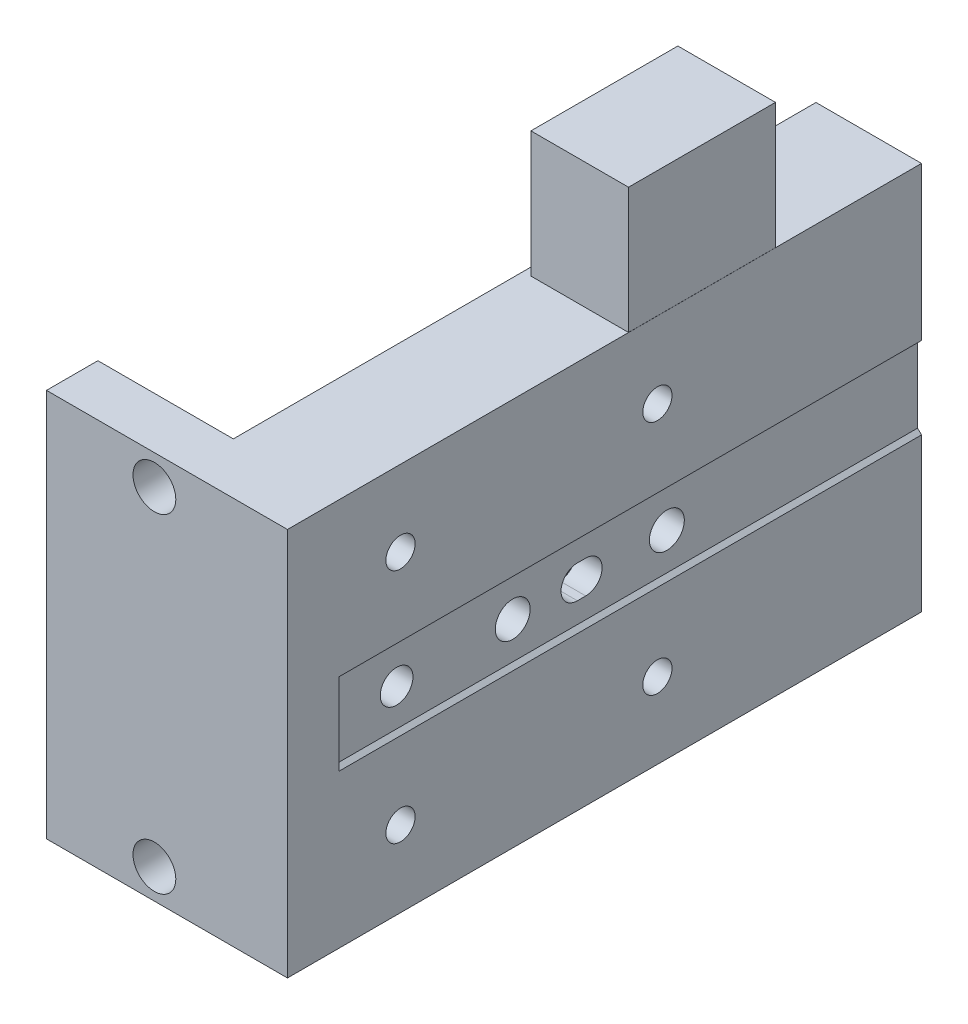
SolidWorks part; units mm, degrees
ref_plane "Front" through (0, 0, 0) normal (0, 0, 1) x (1, 0, 0)
ref_plane "Top" through (0, 0, 0) normal (0, 1, 0) x (1, 0, 0)
ref_plane "Right" through (0, 0, 0) normal (1, 0, 0) x (0, 0, -1)
sketch "Sketch1" plane through (0, 0, -942.5686) normal (0, 0, 1) x (1, 0, 0)
  line L0 (6.9596, 18.9) -> (-6.9596, 18.9) construction
  line L1 (-5.8406, 18.9) -> (17.6094, 18.9)
  line L2 (-5.8406, 18.9) -> (-5.8406, -18.9)
  line L3 (-5.8406, -18.9) -> (17.6094, -18.9)
  line L4 (17.6094, 18.9) -> (17.6094, 3.98)
  line L5 (-5.8406, 0) -> (17.2294, 0) construction
  line L6 (-7.3406, 18.519) -> (-7.3406, 7.3914) construction
  line L8 (-1.7907, -18.9) -> (1.7907, -18.9) construction
  line L9 (17.2294, 3.6) -> (17.2294, -3.6)
  line L10 (17.2294, -3.6) -> (17.6094, -3.98)
  line L11 (17.2294, 3.6) -> (17.6094, 3.98)
  line L12 (17.6094, -3.98) -> (17.6094, -18.9)
  dimension "D1" = 1.5
  dimension "D2" = 24.95
  dimension "D3" = 45
  dimension "D4" = 0.38
  dimension "D5" = 7.2
extrude "Base-Extrude" add sketch "Sketch1" along normal up to surface (5 mm away)
sketch "Sketch3" plane through (0, 0, -942.5686) normal (0, 0, -1) x (-1, 0, 0)
  line L0 (-17.6094, 3.98) -> (-17.6094, 18.9) construction
  line L1 (-17.6094, 18.9) -> (5.8406, 18.9) construction
  line L2 (-17.6094, 3.98) -> (-17.6094, 18.9)
  line L3 (-17.6094, 18.9) -> (-7.3406, 18.9)
  line L4 (5.8406, -18.9) -> (-17.6094, -18.9) construction
  line L5 (-17.6094, -18.9) -> (-17.6094, -3.98) construction
  line L6 (-17.6094, -3.98) -> (-17.2294, -3.6) construction
  line L7 (-17.2294, -3.6) -> (-17.2294, 3.6) construction
  line L8 (-17.2294, 3.6) -> (-17.6094, 3.98) construction
  line L9 (-7.3406, -18.9) -> (-17.6094, -18.9)
  line L10 (-17.6094, -18.9) -> (-17.6094, -3.98)
  line L11 (-17.6094, -3.98) -> (-17.2294, -3.6)
  line L12 (-17.2294, -3.6) -> (-17.2294, 3.6)
  line L13 (-17.2294, 3.6) -> (-17.6094, 3.98)
  line L14 (-7.3406, -7.3914) -> (-7.3406, -18.519) construction
  line L19 (-7.3406, 18.9) -> (-7.3406, -18.9)
extrude "Boss-Extrude1" add sketch "Sketch3" along normal up to surface (56.7 mm away)
sketch "Sketch15" plane through (0, 0, -937.5686) normal (0, 0, 1) x (1, 0, 0)
  line L0 (17.6094, -3.98) -> (17.2294, -3.6) construction
  line L1 (17.2294, -3.6) -> (17.2294, 3.6) construction
  line L2 (17.2294, 3.6) -> (17.6094, 3.98) construction
  line L3 (17.6094, -3.98) -> (17.2294, -3.6)
  line L4 (17.2294, -3.6) -> (17.2294, 3.6)
  line L5 (17.2294, 3.6) -> (17.6094, 3.98)
  line L6 (17.6094, -3.98) -> (17.6094, 3.98)
extrude "Boss-Extrude3" add sketch "Sketch15" against normal up to surface (5 mm away) up to face at (0.75, -4.725, -942.5686)
hole_wizard "3.4 Diameter Hole1" positions "Sketch5" profile "Sketch4" hole size "M3.4" standard "Ansi Metric" end condition through all
sketch "Sketch5" plane through (17.2294, 0, 0) normal (1, 0, 0) x (0, 0, -1)
  point P0 (959.8686, 0)
  point P1 (974.8686, 0)
sketch "Sketch4" plane through (17.2294, 0, -959.8686) normal (0, 1, 0) x (0, 0, -1)
  line L0 (0, 0) -> (0, 23.07)
  line L1 (0, 23.07) -> (1.7, 23.07)
  line L2 (1.7, 23.07) -> (1.7, 0)
  line L5 (1.7, 0) -> (0, 0)
  line L11 (0, -6.35) -> (0, 107.95) construction
  dimension "Thru Hole Dia." = 3.4
  dimension "Thru Hole Depth" = 23.07
hole_wizard "#4-40 Tapped Hole1" positions "Sketch7" profile "Sketch6" tap size "#4-40" standard "Ansi Inch"
sketch "Sketch7" plane through (17.6094, 0, 0) normal (1, 0, 0) x (0, 0, -1)
  point P0 (948.5686, 11.5)
  point P1 (973.5686, 11.5)
  point P3 (948.5686, -11.5)
  point P4 (973.5686, -11.5)
sketch "Sketch6" plane through (17.6094, 11.5, -948.5686) normal (0, 1, 0) x (0, 0, -1)
  line L0 (0, 0) -> (0, 9.5438)
  line L1 (0, 9.5438) -> (1.1303, 8.8646)
  line L2 (1.1303, 8.8646) -> (1.1303, 5.6896)
  line L3 (1.1303, 5.6896) -> (1.4224, 5.6896)
  line L4 (1.4224, 5.6896) -> (1.4224, 0)
  line L5 (1.4224, 0) -> (0, 0)
  line L10 (0, 9.5438) -> (-1.1303, 8.8646) construction
  line L11 (0, -6.35) -> (0, 107.95) construction
  dimension "Tap Drill Dia." = 2.2606
  dimension "Tap Drill Depth" = 8.8646
  dimension "Thread Major Dia." = 2.8448
  dimension "Thread Depth" = 5.6896
  dimension "Drill Angle" = 118
hole_wizard "#4-40 Tapped Hole2" positions "Sketch10" profile "Sketch9" tap size "#8-32" standard "Ansi Inch" end condition through all
sketch "Sketch10" plane through (0, 0, -937.5686) normal (0, 0, 1) x (1, 0, 0)
  line L0 (-7.3406, 18.519) -> (-7.3406, 7.3914) construction
  line L1 (-6.9596, 0) -> (4.6594, 0) construction
  line L2 (-6.9596, 7.0104) -> (-6.9596, -7.0104) construction
  point P0 (4.6594, 16)
  point P1 (4.6594, -16)
  dimension "D1" = 12
  dimension "D2" = 32
sketch "Sketch9" plane through (4.6594, 16, -937.5686) normal (1, 0, 0) x (0, -1, 0)
  line L0 (0, 0) -> (0, 61.7)
  line L1 (0, 61.7) -> (1.7272, 61.7)
  line L3 (1.7272, 61.7) -> (1.7272, 8.3312)
  line L4 (1.7272, 8.3312) -> (2.0828, 8.3312)
  line L5 (2.0828, 8.3312) -> (2.0828, 0)
  line L7 (2.0828, 0) -> (0, 0)
  line L11 (0, -6.35) -> (0, 107.95) construction
  dimension "Thru Tap Drill Dia." = 3.4544
  dimension "Thru Tap Drill Depth" = 61.7
  dimension "Thread Major Dia." = 4.1656
  dimension "Thread Depth" = 8.3312
sketch "Sketch11" plane through (17.2294, 0, 0) normal (1, 0, 0) x (0, 0, -1)
  line L0 (966.5686, 9) -> (966.5686, 0) construction
  line L2 (937.5686, 0) -> (999.2686, 0) construction
  line L4 (968.5686, 0) -> (968.5686, 9) construction
  line L5 (964.5686, 0) -> (964.5686, 9) construction
  line L6 (966.1625, 1.5939) -> (966.9748, 1.5939)
  line L7 (966.1625, -1.5938) -> (966.9748, -1.5938)
  arc A0 (966.9748, -1.5938) -> (966.9748, 1.5939) centre (966.9748, 0) ccw
  arc A1 (966.1625, 1.5939) -> (966.1625, -1.5938) centre (966.1625, 0) ccw
  dimension "D1" = 3.1877
  dimension "D2" = 4
extrude "Cut-Extrude1" cut sketch "Sketch11" against normal blind 2.54
hole_wizard "Hole1" positions "Sketch13" profile "Sketch12" legacy
sketch "Sketch13" plane through (17.2294, 0, 0) normal (1, 0, 0) x (0, 0, -1)
  line L0 (937.5686, 0) -> (999.2686, 0) construction
  point P0 (948.5686, 0)
sketch "Sketch12" plane through (17.2294, 0, -948.5686) normal (0, 1, 0) x (0, 0, -1)
  line L0 (0, 0) -> (0, 2.54)
  line L1 (0, 2.54) -> (1.5939, 2.54)
  line L2 (1.5939, 2.54) -> (1.5939, 0)
  line L3 (1.5939, 0) -> (0, 0)
  line L4 (0, 110) -> (0, -10) construction
  dimension "Diameter" = 3.1877
  dimension "Depth" = 2.54
sketch "Sketch2" plane through (0, 0, -937.5686) normal (0, 0, 1) x (1, 0, 0)
  line L0 (17.6094, -18.9) -> (17.6094, 18.9) construction
  line L1 (17.6094, 18.9) -> (-5.8406, 18.9) construction
  circle A2 centre (0, 8.6106) radius 2.25
  circle A3 centre (0, -8.6106) radius 2.25
  circle A4 centre (13.1094, 13.87) radius 3.96
  circle A5 centre (13.1094, -13.34) radius 3.96
  dimension "D1" = 7.92
  dimension "D4" = 4.5
  dimension "D2" = 27.21
  dimension "D3" = 4.5
  dimension "D5" = 5.03
sketch "Sketch14" plane through (0, 18.9, 0) normal (0, 1, 0) x (-1, 0, 0)
  line L1 (-17.5994, -970.7686) -> (-8.0994, -970.7686)
  line L2 (-17.5994, -970.7686) -> (-17.5994, -985.0686)
  line L3 (-17.5994, -985.0686) -> (-8.0994, -985.0686)
  line L4 (-8.0994, -970.7686) -> (-8.0994, -985.0686)
  line L5 (-17.6094, -937.5686) -> (-17.6094, -999.2686) construction
  line L7 (-8.925, -970.7686) -> (8.925, -970.7686) construction
  dimension "D1" = 14.3
  dimension "D2" = 9.5
  dimension "D3" = 0.01
extrude "Boss-Extrude2" add sketch "Sketch14" along normal blind 12.24
